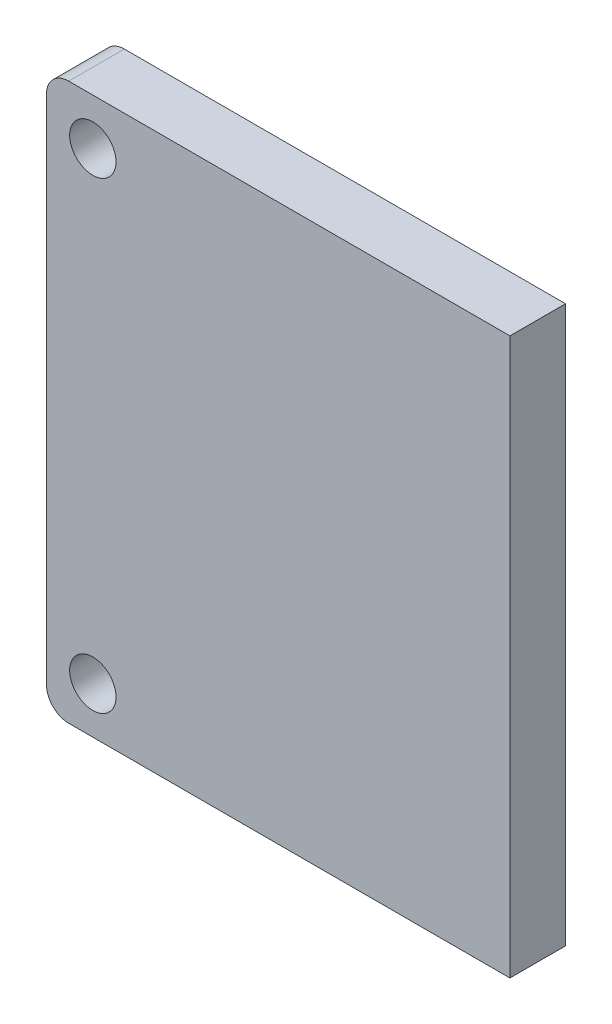
SolidWorks part; units mm, degrees
ref_plane "前视基准面" through (0, 0, 0) normal (0, 0, 1) x (1, 0, 0)
ref_plane "上视基准面" through (0, 0, 0) normal (0, 1, 0) x (1, 0, 0)
ref_plane "右视基准面" through (0, 0, 0) normal (1, 0, 0) x (0, 0, -1)
sketch "草图1" plane through (0, 0, 0) normal (0, 0, 1) x (1, 0, 0)
  line L0 (25, 30) -> (25, 0)
  line L8 (1.2, 0) -> (25, 0)
  line L10 (25, 30) -> (1.2, 30)
  line L11 (0, 28.8) -> (0, 1.2)
  circle A2 centre (2.5, 2.5) radius 1.25
  circle A3 centre (2.5, 27.5) radius 1.25
  arc A8 (0, 1.2) -> (1.2, 0) centre (1.1984, 1.1984) ccw
  arc A11 (1.2, 30) -> (0, 28.8) centre (1.1984, 28.8016) ccw
extrude "凸台-拉伸1" add sketch "草图1" along normal blind 3
